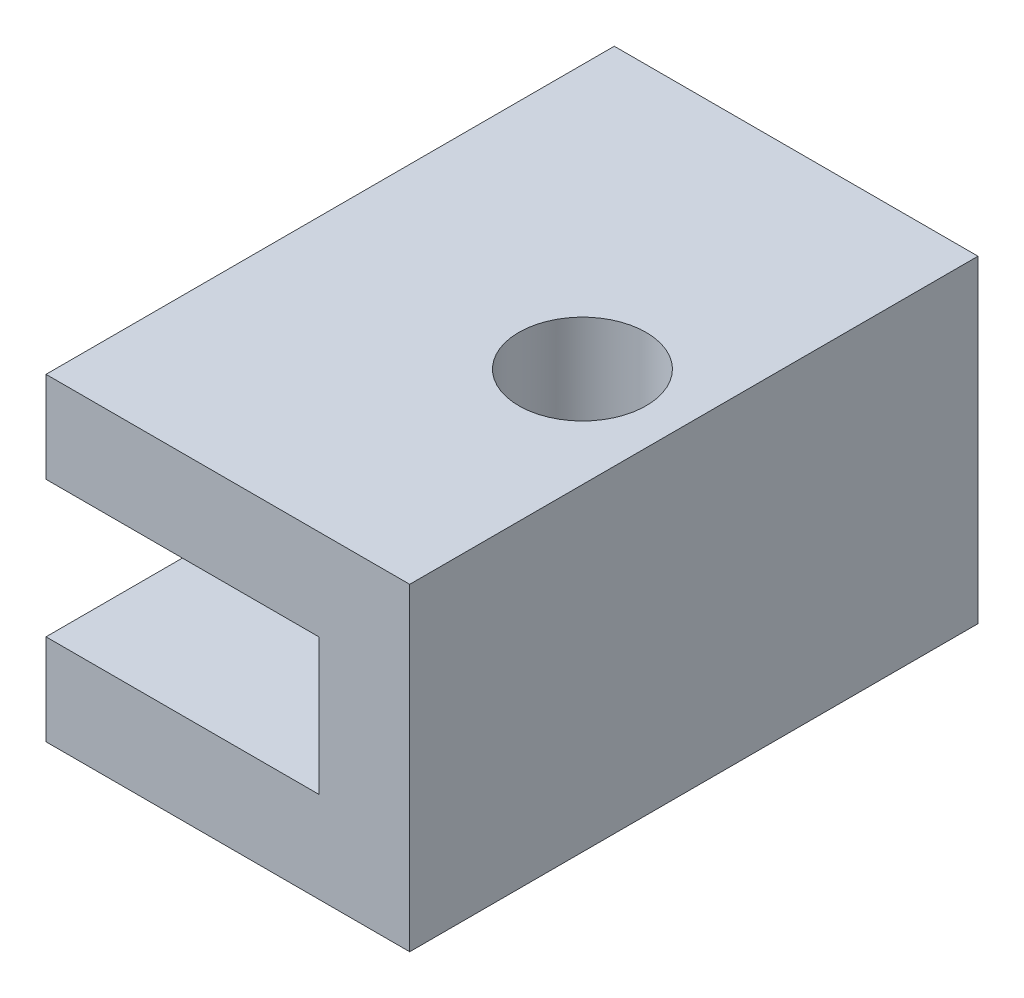
SolidWorks part; units mm, degrees
ref_plane "Front Plane" through (0, 0, 0) normal (0, 0, 1) x (1, 0, 0)
ref_plane "Top Plane" through (0, 0, 0) normal (0, 1, 0) x (1, 0, 0)
ref_plane "Right Plane" through (0, 0, 0) normal (1, 0, 0) x (0, 0, -1)
sketch "Sketch1" plane through (0, 0, 0) normal (0, 0, 1) x (1, 0, 0)
  line L0 (0, 0) -> (8, 0)
  line L1 (8, 0) -> (8, 7)
  line L2 (8, 7) -> (0, 7)
  line L3 (0, 7) -> (0, 5)
  line L4 (0, 5) -> (6, 5)
  line L5 (6, 5) -> (6, 2)
  line L6 (6, 2) -> (0, 2)
  line L7 (0, 2) -> (0, 0)
  point P4 (3, 5)
  dimension "D1" = 2
  dimension "D2" = 2
  dimension "D3" = 2
  dimension "D4" = 7
  dimension "D5" = 8
extrude "Boss-Extrude1" add sketch "Sketch1" along normal blind 12.5
sketch "Sketch2" plane through (0, 7, 0) normal (0, 1, 0) x (1, 0, 0)
  line L2 (0, -12.5) -> (0, 0) construction
  line L3 (8, -12.5) -> (0, -12.5) construction
  circle A1 centre (5.8, -6.5) radius 1.4
  dimension "D1" = 5.8
  dimension "D2" = 6
extrude "Cut-Extrude1" cut sketch "Sketch2" against normal through all
